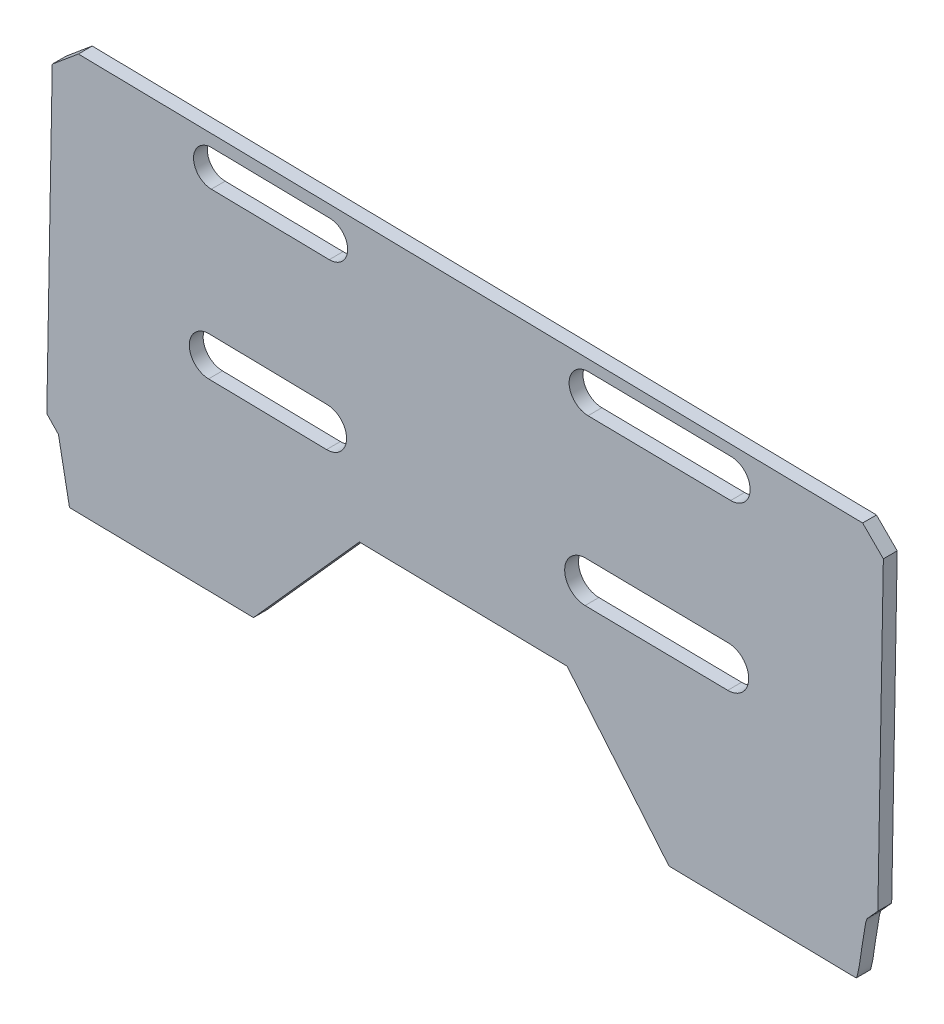
SolidWorks part; units mm, degrees
ref_plane "Front Plane" through (0, 0, 0) normal (0, 0, 1) x (1, 0, 0)
ref_plane "Top Plane" through (0, 0, 0) normal (0, 1, 0) x (1, 0, 0)
ref_plane "Right Plane" through (0, 0, 0) normal (1, 0, 0) x (0, 0, -1)
sketch "Sketch1" plane through (0, 0, 0) normal (0, 0, 1) x (1, 0, 0)
  line L0 (80.9506, 77.0853) -> (80.9506, 77.0854)
  line L9 (38.3776, 77.837) -> (38.3776, 77.8369)
  line L10 (38.3776, 77.8369) -> (38.3776, 77.8368)
  line L36 (220.7298, 15.384) -> (220.7298, 15.3841)
  line L37 (216.802, 19.4549) -> (209.3614, 19.4432)
  line L38 (209.3614, 19.4432) -> (205.3621, 19.5146)
  line L39 (205.3621, 19.5146) -> (201.3627, 19.5861)
  line L40 (201.3627, 19.5861) -> (197.3634, 19.6576)
  line L41 (197.3634, 19.6576) -> (193.3639, 19.7294)
  line L42 (193.3639, 19.7294) -> (189.3645, 19.8005)
  line L43 (189.3645, 19.8005) -> (185.3652, 19.872)
  line L44 (185.3652, 19.872) -> (181.3658, 19.9435)
  line L45 (177.2951, 16.0157) -> (177.2951, 16.0156)
  line L46 (181.2229, 11.9448) -> (185.2223, 11.8733)
  line L47 (185.2223, 11.8733) -> (189.2217, 11.8018)
  line L48 (189.2217, 11.8018) -> (193.221, 11.7303)
  line L49 (193.221, 11.7303) -> (197.2204, 11.6589)
  line L50 (197.2204, 11.6589) -> (201.2199, 11.5874)
  line L51 (201.2199, 11.5874) -> (205.2192, 11.5159)
  line L52 (205.2192, 11.5159) -> (209.2186, 11.4444)
  line L53 (209.2186, 11.4444) -> (216.6591, 11.4563)
  line L54 (221.7899, 74.7037) -> (221.79, 74.7038)
  line L55 (221.79, 74.7038) -> (221.79, 74.7039)
  line L56 (217.8622, 78.7746) -> (210.4216, 78.7629)
  line L57 (210.4216, 78.7629) -> (206.4222, 78.8344)
  line L58 (206.4222, 78.8344) -> (202.4228, 78.9058)
  line L59 (202.4228, 78.9058) -> (198.4235, 78.9773)
  line L60 (198.4235, 78.9773) -> (194.424, 79.0488)
  line L61 (194.424, 79.0488) -> (190.4247, 79.1203)
  line L62 (190.4247, 79.1203) -> (186.4253, 79.1917)
  line L63 (186.4253, 79.1917) -> (182.4259, 79.2632)
  line L64 (178.3552, 75.3354) -> (178.3552, 75.3353)
  line L65 (178.3552, 75.3353) -> (178.3552, 75.3352)
  line L66 (182.283, 71.2645) -> (186.2824, 71.193)
  line L67 (186.2824, 71.193) -> (190.2818, 71.1215)
  line L68 (190.2818, 71.1215) -> (194.2812, 71.0501)
  line L69 (194.2812, 71.0501) -> (198.2805, 70.9786)
  line L70 (198.2805, 70.9786) -> (202.28, 70.9071)
  line L71 (202.28, 70.9071) -> (206.2794, 70.8356)
  line L72 (206.2794, 70.8356) -> (210.2787, 70.7642)
  line L73 (210.2787, 70.7642) -> (217.7192, 70.7759)
  line L102 (-21.1101, -28.5266) -> (-16.8985, -32.9542)
  line L103 (-16.8985, -32.9542) -> (-12.921, -53.8052)
  line L106 (53.4882, -54.9921) -> (91.6986, -12.2556)
  line L109 (166.6866, -13.5957) -> (203.4642, -57.6722)
  line L112 (38.3776, 77.8368) -> (80.9506, 77.0855) construction
  line L113 (38.4927, 84.3588) -> (81.0657, 83.6075)
  line L114 (38.2625, 71.3148) -> (80.8355, 70.5635)
  line L118 (178.3552, 75.3352) -> (221.79, 74.7038) construction
  line L119 (178.4138, 79.3664) -> (221.8486, 78.735)
  line L120 (178.2966, 71.304) -> (221.7314, 70.6726)
  line L121 (177.2951, 16.0157) -> (220.7298, 15.384) construction
  line L122 (177.3537, 20.0463) -> (220.7884, 19.4146)
  line L123 (177.2365, 11.9851) -> (220.6712, 11.3534)
  line L127 (174.324, 75.3938) -> (225.8212, 74.6452) construction
  line L128 (174.4245, 82.307) -> (225.9217, 81.5584)
  line L129 (174.2235, 68.4806) -> (225.7207, 67.732)
  line L130 (173.2645, 16.0743) -> (224.7604, 15.3254) construction
  line L131 (173.373, 23.5344) -> (224.8689, 22.7854)
  line L132 (173.156, 8.6143) -> (224.6519, 7.8653)
  line L136 (-19.1403, 81.699) -> (-21.1101, -28.5266)
  line L137 (-19.1403, 81.699) -> (-9.7117, 89.5727)
  line L138 (-9.7117, 89.5727) -> (273.3449, 84.5141)
  line L139 (273.3449, 84.5141) -> (280.8244, 77.0441)
  line L140 (280.8244, 77.0441) -> (278.8388, -34.0633)
  line L141 (271.018, -58.8795) -> (203.4642, -57.6722)
  line L142 (166.6866, -13.5957) -> (91.6986, -12.2556)
  line L143 (53.4882, -54.9921) -> (-12.921, -53.8052)
  line L145 (79.9899, 17.811) -> (37.4177, 18.6174) construction
  line L146 (79.8555, 10.7203) -> (37.2834, 11.5266)
  line L147 (80.1242, 24.9018) -> (37.552, 25.7082)
  arc A0 (38.4927, 84.3588) -> (38.2625, 71.3148) centre (38.3776, 77.8368) ccw
  arc A1 (80.8355, 70.5635) -> (81.0657, 83.6075) centre (80.9506, 77.0855) ccw
  arc A4 (178.4138, 79.3664) -> (178.2966, 71.304) centre (178.3552, 75.3352) ccw
  arc A5 (221.7314, 70.6726) -> (221.8486, 78.735) centre (221.79, 74.7038) ccw
  arc A6 (177.3537, 20.0463) -> (177.2365, 11.9851) centre (177.2951, 16.0157) ccw
  arc A7 (220.6712, 11.3534) -> (220.7884, 19.4146) centre (220.7298, 15.384) ccw
  arc A10 (174.4245, 82.307) -> (174.2235, 68.4806) centre (174.324, 75.3938) ccw
  arc A11 (225.7207, 67.732) -> (225.9217, 81.5584) centre (225.8212, 74.6452) ccw
  arc A12 (173.373, 23.5344) -> (173.156, 8.6143) centre (173.2645, 16.0743) ccw
  arc A13 (224.6519, 7.8653) -> (224.8689, 22.7854) centre (224.7604, 15.3254) ccw
  arc A16 (79.8555, 10.7203) -> (80.1242, 24.9018) centre (79.9899, 17.811) ccw
  arc A17 (37.552, 25.7082) -> (37.2834, 11.5266) centre (37.4177, 18.6174) ccw
  spline S64 degree 3 poles (220.7298, 15.3842) (220.7347, 15.6591) (220.7113, 15.9287) (220.6626, 16.1891) knots 0.123077 0.123077 0.123077 0.123077 0.138462 0.138462 0.138462 0.138462
  spline S65 degree 3 poles (220.6626, 16.1891) (220.6139, 16.4496) (220.5389, 16.7023) (220.442, 16.9428) knots 0.138462 0.138462 0.138462 0.138462 0.153846 0.153846 0.153846 0.153846
  spline S66 degree 3 poles (220.442, 16.9428) (220.345, 17.1833) (220.2244, 17.4134) (220.0843, 17.6287) knots 0.153846 0.153846 0.153846 0.153846 0.169231 0.169231 0.169231 0.169231
  spline S67 degree 3 poles (220.0843, 17.6287) (219.9443, 17.8438) (219.7833, 18.0455) (219.6056, 18.2297) knots 0.169231 0.169231 0.169231 0.169231 0.184615 0.184615 0.184615 0.184615
  spline S68 degree 3 poles (219.6056, 18.2297) (219.4278, 18.4139) (219.232, 18.582) (219.0219, 18.7297) knots 0.184615 0.184615 0.184615 0.184615 0.2 0.2 0.2 0.2
  spline S69 degree 3 poles (219.0219, 18.7297) (218.8119, 18.8773) (218.5862, 19.0061) (218.3494, 19.1116) knots 0.2 0.2 0.2 0.2 0.215385 0.215385 0.215385 0.215385
  spline S70 degree 3 poles (218.3494, 19.1116) (218.1123, 19.2172) (217.8625, 19.3009) (217.6039, 19.3589) knots 0.215385 0.215385 0.215385 0.215385 0.230769 0.230769 0.230769 0.230769
  spline S71 degree 3 poles (217.6039, 19.3589) (217.3453, 19.4169) (217.0766, 19.4552) (216.802, 19.4549) knots 0.230769 0.230769 0.230769 0.230769 0.246154 0.246154 0.246154 0.246154
  spline S72 degree 3 poles (181.3658, 19.9435) (181.0911, 19.9484) (180.8216, 19.9251) (180.5609, 19.8763) knots 0.369231 0.369231 0.369231 0.369231 0.384615 0.384615 0.384615 0.384615
  spline S73 degree 3 poles (180.5609, 19.8763) (180.3002, 19.8274) (180.048, 19.7529) (179.8072, 19.6557) knots 0.384615 0.384615 0.384615 0.384615 0.4 0.4 0.4 0.4
  spline S74 degree 3 poles (179.8072, 19.6557) (179.5664, 19.5585) (179.3369, 19.4383) (179.1214, 19.298) knots 0.4 0.4 0.4 0.4 0.415385 0.415385 0.415385 0.415385
  spline S75 degree 3 poles (179.1214, 19.298) (178.906, 19.1577) (178.7045, 18.997) (178.5203, 18.8192) knots 0.415385 0.415385 0.415385 0.415385 0.430769 0.430769 0.430769 0.430769
  spline S76 degree 3 poles (178.5203, 18.8192) (178.336, 18.6415) (178.168, 18.4457) (178.0204, 18.2355) knots 0.430769 0.430769 0.430769 0.430769 0.446154 0.446154 0.446154 0.446154
  spline S77 degree 3 poles (178.0204, 18.2355) (177.8727, 18.0254) (177.7441, 17.8001) (177.6384, 17.5629) knots 0.446154 0.446154 0.446154 0.446154 0.461538 0.461538 0.461538 0.461538
  spline S78 degree 3 poles (177.6384, 17.5629) (177.5326, 17.3258) (177.4493, 17.0764) (177.3911, 16.8176) knots 0.461538 0.461538 0.461538 0.461538 0.476923 0.476923 0.476923 0.476923
  spline S79 degree 3 poles (177.3911, 16.8176) (177.333, 16.5588) (177.3, 16.2903) (177.2951, 16.0157) knots 0.476923 0.476923 0.476923 0.476923 0.492308 0.492308 0.492308 0.492308
  spline S80 degree 3 poles (177.2951, 16.0155) (177.2902, 15.7405) (177.3135, 15.4714) (177.3623, 15.2107) knots 0.615385 0.615385 0.615385 0.615385 0.630769 0.630769 0.630769 0.630769
  spline S81 degree 3 poles (177.3623, 15.2107) (177.4112, 14.9499) (177.4858, 14.6977) (177.5829, 14.457) knots 0.630769 0.630769 0.630769 0.630769 0.646154 0.646154 0.646154 0.646154
  spline S82 degree 3 poles (177.5829, 14.457) (177.6799, 14.2163) (177.8004, 13.9865) (177.9406, 13.7713) knots 0.646154 0.646154 0.646154 0.646154 0.661538 0.661538 0.661538 0.661538
  spline S83 degree 3 poles (177.9406, 13.7713) (178.0807, 13.5561) (178.2415, 13.3543) (178.4193, 13.1701) knots 0.661538 0.661538 0.661538 0.661538 0.676923 0.676923 0.676923 0.676923
  spline S84 degree 3 poles (178.4193, 13.1701) (178.597, 12.9858) (178.7929, 12.8179) (179.003, 12.6702) knots 0.676923 0.676923 0.676923 0.676923 0.692308 0.692308 0.692308 0.692308
  spline S85 degree 3 poles (179.003, 12.6702) (179.2131, 12.5225) (179.4384, 12.3939) (179.6756, 12.2882) knots 0.692308 0.692308 0.692308 0.692308 0.707692 0.707692 0.707692 0.707692
  spline S86 degree 3 poles (179.6756, 12.2882) (179.9127, 12.1824) (180.1622, 12.0987) (180.4209, 12.0408) knots 0.707692 0.707692 0.707692 0.707692 0.723077 0.723077 0.723077 0.723077
  spline S87 degree 3 poles (180.4209, 12.0408) (180.6794, 11.9829) (180.9478, 11.9497) (181.2229, 11.9448) knots 0.723077 0.723077 0.723077 0.723077 0.738462 0.738462 0.738462 0.738462
  spline S88 degree 3 poles (216.6591, 11.4563) (216.934, 11.4567) (217.2035, 11.4749) (217.4639, 11.5235) knots 0.861538 0.861538 0.861538 0.861538 0.876923 0.876923 0.876923 0.876923
  spline S89 degree 3 poles (217.4639, 11.5235) (217.7243, 11.5722) (217.977, 11.647) (218.2176, 11.7441) knots 0.876923 0.876923 0.876923 0.876923 0.892308 0.892308 0.892308 0.892308
  spline S90 degree 3 poles (218.2176, 11.7441) (218.4582, 11.8411) (218.6879, 11.9614) (218.9034, 12.1017) knots 0.892308 0.892308 0.892308 0.892308 0.907692 0.907692 0.907692 0.907692
  spline S91 degree 3 poles (218.9034, 12.1017) (219.1187, 12.2421) (219.3202, 12.4027) (219.5046, 12.5806) knots 0.907692 0.907692 0.907692 0.907692 0.923077 0.923077 0.923077 0.923077
  spline S92 degree 3 poles (219.5046, 12.5806) (219.6889, 12.7585) (219.8568, 12.9541) (220.0045, 13.1642) knots 0.923077 0.923077 0.923077 0.923077 0.938462 0.938462 0.938462 0.938462
  spline S93 degree 3 poles (220.0045, 13.1642) (220.1522, 13.3744) (220.2809, 13.5996) (220.3865, 13.8368) knots 0.938462 0.938462 0.938462 0.938462 0.953846 0.953846 0.953846 0.953846
  spline S94 degree 3 poles (220.3865, 13.8368) (220.4923, 14.0738) (220.5759, 14.3235) (220.6339, 14.5821) knots 0.953846 0.953846 0.953846 0.953846 0.969231 0.969231 0.969231 0.969231
  spline S95 degree 3 poles (220.6339, 14.5821) (220.6918, 14.8405) (220.7259, 15.109) (220.7298, 15.384) knots 0.969231 0.969231 0.969231 0.969231 1 1 1 1
  spline S96 degree 3 poles (221.79, 74.7039) (221.7949, 74.9789) (221.7716, 75.2483) (221.7227, 75.5088) knots 0.123077 0.123077 0.123077 0.123077 0.138462 0.138462 0.138462 0.138462
  spline S97 degree 3 poles (221.7227, 75.5088) (221.674, 75.7695) (221.5993, 76.0218) (221.5022, 76.2625) knots 0.138462 0.138462 0.138462 0.138462 0.153846 0.153846 0.153846 0.153846
  spline S98 degree 3 poles (221.5022, 76.2625) (221.405, 76.5033) (221.2846, 76.7331) (221.1445, 76.9483) knots 0.153846 0.153846 0.153846 0.153846 0.169231 0.169231 0.169231 0.169231
  spline S99 degree 3 poles (221.1445, 76.9483) (221.0042, 77.1636) (220.8436, 77.3652) (220.6657, 77.5494) knots 0.169231 0.169231 0.169231 0.169231 0.184615 0.184615 0.184615 0.184615
  spline S100 degree 3 poles (220.6657, 77.5494) (220.4879, 77.7339) (220.2922, 77.9015) (220.0821, 78.0494) knots 0.184615 0.184615 0.184615 0.184615 0.2 0.2 0.2 0.2
  spline S101 degree 3 poles (220.0821, 78.0494) (219.8719, 78.1971) (219.6464, 78.3257) (219.4095, 78.4313) knots 0.2 0.2 0.2 0.2 0.215385 0.215385 0.215385 0.215385
  spline S102 degree 3 poles (219.4095, 78.4313) (219.1722, 78.537) (218.9227, 78.6205) (218.6641, 78.6786) knots 0.215385 0.215385 0.215385 0.215385 0.230769 0.230769 0.230769 0.230769
  spline S103 degree 3 poles (218.6641, 78.6786) (218.4053, 78.7367) (218.1369, 78.775) (217.8622, 78.7746) knots 0.230769 0.230769 0.230769 0.230769 0.246154 0.246154 0.246154 0.246154
  spline S104 degree 3 poles (182.4259, 79.2632) (182.1509, 79.2681) (181.8817, 79.2448) (181.621, 79.196) knots 0.369231 0.369231 0.369231 0.369231 0.384615 0.384615 0.384615 0.384615
  spline S105 degree 3 poles (181.621, 79.196) (181.3603, 79.1471) (181.1081, 79.0726) (180.8673, 78.9754) knots 0.384615 0.384615 0.384615 0.384615 0.4 0.4 0.4 0.4
  spline S106 degree 3 poles (180.8673, 78.9754) (180.6266, 78.8782) (180.397, 78.758) (180.1815, 78.6177) knots 0.4 0.4 0.4 0.4 0.415385 0.415385 0.415385 0.415385
  spline S107 degree 3 poles (180.1815, 78.6177) (179.9661, 78.4774) (179.7648, 78.3168) (179.5804, 78.139) knots 0.415385 0.415385 0.415385 0.415385 0.430769 0.430769 0.430769 0.430769
  spline S108 degree 3 poles (179.5804, 78.139) (179.396, 77.961) (179.2284, 77.7655) (179.0805, 77.5552) knots 0.430769 0.430769 0.430769 0.430769 0.446154 0.446154 0.446154 0.446154
  spline S109 degree 3 poles (179.0805, 77.5552) (178.9327, 77.3449) (178.8043, 77.1198) (178.6985, 76.8826) knots 0.446154 0.446154 0.446154 0.446154 0.461538 0.461538 0.461538 0.461538
  spline S110 degree 3 poles (178.6985, 76.8826) (178.5927, 76.6455) (178.5094, 76.3961) (178.4512, 76.1373) knots 0.461538 0.461538 0.461538 0.461538 0.476923 0.476923 0.476923 0.476923
  spline S111 degree 3 poles (178.4512, 76.1373) (178.3931, 75.8785) (178.3601, 75.6103) (178.3552, 75.3354) knots 0.476923 0.476923 0.476923 0.476923 0.492308 0.492308 0.492308 0.492308
  spline S112 degree 3 poles (178.3552, 75.3352) (178.3503, 75.0603) (178.3736, 74.7911) (178.4224, 74.5304) knots 0.615385 0.615385 0.615385 0.615385 0.630769 0.630769 0.630769 0.630769
  spline S113 degree 3 poles (178.4224, 74.5304) (178.4713, 74.2697) (178.5458, 74.0176) (178.643, 73.7767) knots 0.630769 0.630769 0.630769 0.630769 0.646154 0.646154 0.646154 0.646154
  spline S114 degree 3 poles (178.643, 73.7767) (178.7402, 73.536) (178.8604, 73.3065) (179.0007, 73.091) knots 0.646154 0.646154 0.646154 0.646154 0.661538 0.661538 0.661538 0.661538
  spline S115 degree 3 poles (179.0007, 73.091) (179.141, 72.8757) (179.3015, 72.6742) (179.4794, 72.4898) knots 0.661538 0.661538 0.661538 0.661538 0.676923 0.676923 0.676923 0.676923
  spline S116 degree 3 poles (179.4794, 72.4898) (179.6574, 72.3055) (179.8529, 72.1378) (180.0631, 71.99) knots 0.676923 0.676923 0.676923 0.676923 0.692308 0.692308 0.692308 0.692308
  spline S117 degree 3 poles (180.0631, 71.99) (180.2734, 71.8421) (180.4985, 71.7136) (180.7357, 71.6079) knots 0.692308 0.692308 0.692308 0.692308 0.707692 0.707692 0.707692 0.707692
  spline S118 degree 3 poles (180.7357, 71.6079) (180.9728, 71.5021) (181.2223, 71.4187) (181.481, 71.3605) knots 0.707692 0.707692 0.707692 0.707692 0.723077 0.723077 0.723077 0.723077
  spline S119 degree 3 poles (181.481, 71.3605) (181.7397, 71.3025) (182.0079, 71.2694) (182.283, 71.2645) knots 0.723077 0.723077 0.723077 0.723077 0.738462 0.738462 0.738462 0.738462
  spline S120 degree 3 poles (217.7192, 70.7759) (217.9941, 70.7764) (218.2635, 70.7944) (218.524, 70.8431) knots 0.861538 0.861538 0.861538 0.861538 0.876923 0.876923 0.876923 0.876923
  spline S121 degree 3 poles (218.524, 70.8431) (218.7847, 70.892) (219.037, 70.9666) (219.2777, 71.0637) knots 0.876923 0.876923 0.876923 0.876923 0.892308 0.892308 0.892308 0.892308
  spline S122 degree 3 poles (219.2777, 71.0637) (219.5184, 71.1609) (219.7481, 71.281) (219.9635, 71.4214) knots 0.892308 0.892308 0.892308 0.892308 0.907692 0.907692 0.907692 0.907692
  spline S123 degree 3 poles (219.9635, 71.4214) (220.179, 71.5618) (220.3804, 71.7224) (220.5648, 71.9003) knots 0.907692 0.907692 0.907692 0.907692 0.923077 0.923077 0.923077 0.923077
  spline S124 degree 3 poles (220.5648, 71.9003) (220.7491, 72.0782) (220.9168, 72.2737) (221.0647, 72.4839) knots 0.923077 0.923077 0.923077 0.923077 0.938462 0.938462 0.938462 0.938462
  spline S125 degree 3 poles (221.0647, 72.4839) (221.2124, 72.6941) (221.341, 72.9193) (221.4466, 73.1566) knots 0.938462 0.938462 0.938462 0.938462 0.953846 0.953846 0.953846 0.953846
  spline S126 degree 3 poles (221.4466, 73.1566) (221.5524, 73.3935) (221.636, 73.643) (221.694, 73.9018) knots 0.953846 0.953846 0.953846 0.953846 0.969231 0.969231 0.969231 0.969231
  spline S127 degree 3 poles (221.694, 73.9018) (221.7521, 74.1603) (221.786, 74.4287) (221.7899, 74.7037) knots 0.969231 0.969231 0.969231 0.969231 1 1 1 1
  spline S128 degree 3 poles (271.018, -58.8795) (272.2824, -57.4808) (273.7811, -39.6586) (275.0455, -38.2598) knots 0.926829 0.926829 0.926829 0.926829 0.95122 0.95122 0.95122 0.95122
  spline S129 degree 3 poles (275.0455, -38.2598) (276.3099, -36.861) (277.5743, -35.4621) (278.8388, -34.0633) knots 0.95122 0.95122 0.95122 0.95122 1 1 1 1
  point P3 (0, 0)
  point P61 (37.3686, 17.5629)
  point P218 (58.7038, 18.2142)
  point P247 (59.6641, 77.4612)
  point P257 (200.0726, 75.0195)
  point P262 (199.0125, 15.6999)
  point P274 (200.0726, 75.0195)
  point P281 (199.0125, 15.6999)
  dimension "D1" = 42.5721
extrude "Boss-Extrude1" add sketch "Sketch1" along normal blind 5
scale "Scale3" scale about origin uniform scaling yes scale factor 0.7
